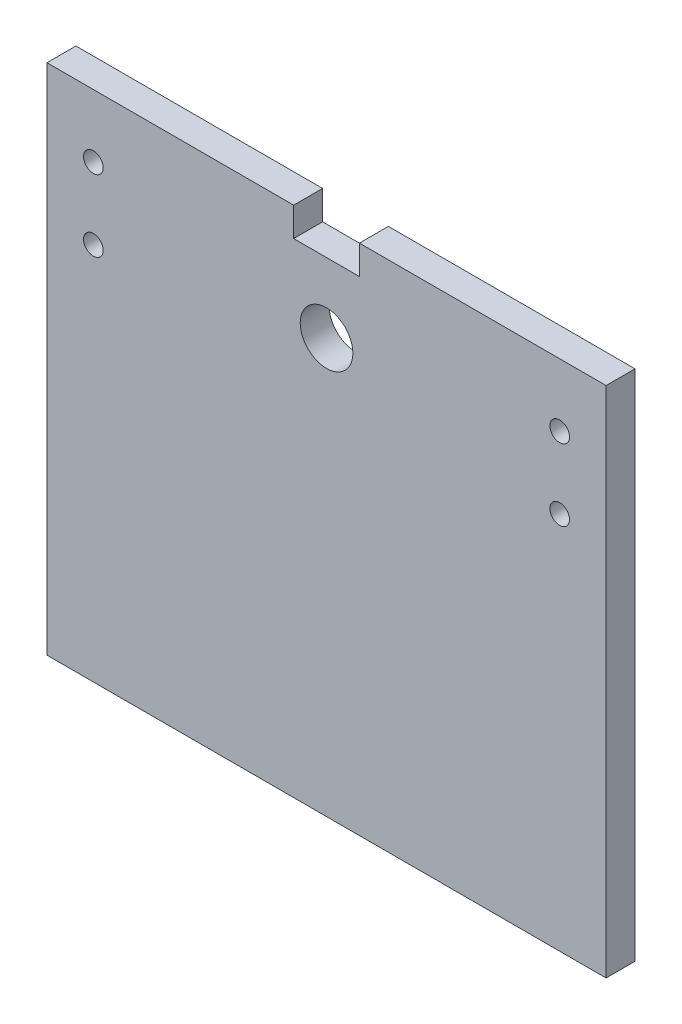
SolidWorks part; units mm, degrees
ref_plane "Front Plane" through (0, 0, 0) normal (0, 0, 1) x (1, 0, 0)
ref_plane "Top Plane" through (0, 0, 0) normal (0, 1, 0) x (1, 0, 0)
ref_plane "Right Plane" through (0, 0, 0) normal (1, 0, 0) x (0, 0, -1)
sketch "Sketch1" plane through (0, 0, 0) normal (0, 0, 1) x (1, 0, 0)
  line L0 (-6.35, 49.53) -> (-6.35, 43.942)
  line L1 (-53.975, -49.53) -> (53.975, -49.53)
  line L2 (-53.975, -49.53) -> (-53.975, 49.53)
  line L3 (-53.975, 49.53) -> (-6.35, 49.53)
  line L4 (53.975, -49.53) -> (53.975, 49.53)
  line L5 (-53.975, -49.53) -> (53.975, 49.53) construction
  line L6 (-53.975, 49.53) -> (53.975, -49.53) construction
  line L7 (-6.35, 43.942) -> (6.35, 43.942)
  line L8 (6.35, 43.942) -> (6.35, 49.53)
  line L9 (6.35, 49.53) -> (53.975, 49.53)
  point P0 (0, 0)
  dimension "D1" = 107.95
  dimension "D2" = 99.06
  dimension "D3" = 5.588
  dimension "D4" = 12.7
extrude "Boss-Extrude1" add sketch "Sketch1" along normal mid plane 5.588
sketch "Sketch2" plane through (0, 0, -2.794) normal (0, 0, -1) x (-1, 0, 0)
  point P0 (-45.0148, 37.3948)
  point P1 (-45.0148, 23.5652)
  point P3 (45.0148, 37.3948)
  point P5 (45.0148, 23.5652)
hole_wizard "#6 Clearance Hole1" positions "Sketch3" profile "Sketch4" hole size "#6" standard "ANSI Inch" end condition through all
sketch "Sketch3" plane through (0, 0, -2.794) normal (0, 0, -1) x (-1, 0, 0)
  point P0 (-45.0148, 37.3948)
  point P3 (-45.0148, 23.5652)
  point P6 (45.0148, 37.3948)
  point P9 (45.0148, 23.5652)
sketch "Sketch4" plane through (45.0148, 37.3948, -2.794) normal (1, 0, 0) x (0, 1, 0)
  line L0 (0, 0) -> (0, 5.588)
  line L1 (0, 5.588) -> (1.8986, 5.588)
  line L2 (1.8986, 5.588) -> (1.8986, 0)
  line L5 (1.8986, 0) -> (0, 0)
  line L11 (0, -6.35) -> (0, 107.95) construction
  dimension "Thru Hole Dia." = 3.7973
  dimension "Thru Hole Depth" = 5.588
sketch "Sketch5" plane through (0, 0, -2.794) normal (0, 0, -1) x (-1, 0, 0)
  line L0 (53.975, 49.53) -> (53.975, -49.53) construction
  line L1 (53.975, -49.53) -> (-53.975, -49.53) construction
  circle A0 centre (0, 30.48) radius 5.08
  dimension "D1" = 10.16
  dimension "D2" = 53.975
  dimension "D3" = 80.01
extrude "Cut-Extrude1" cut sketch "Sketch5" against normal up to next
